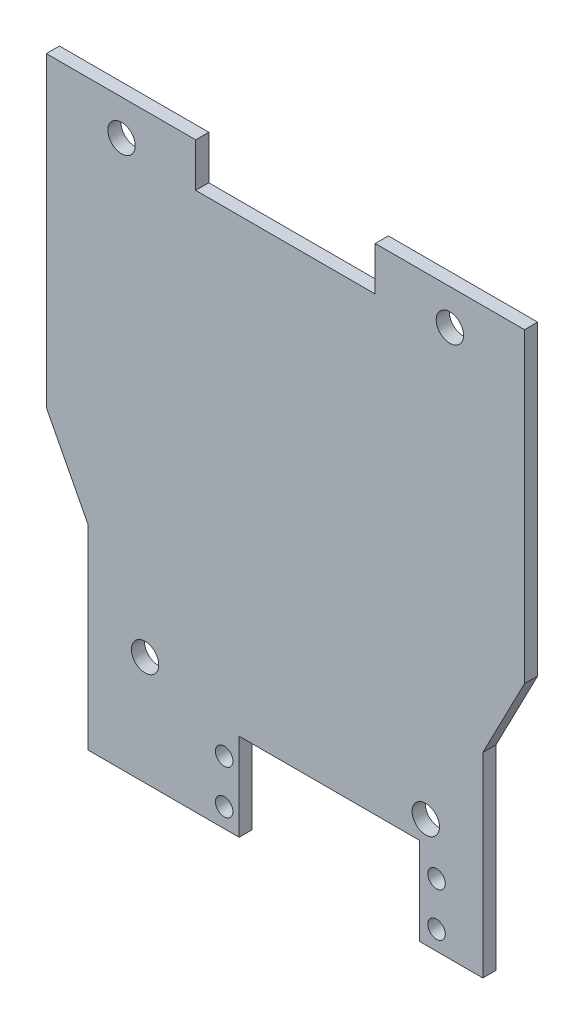
SolidWorks part; units mm, degrees
ref_plane "Front Plane" through (0, 0, 0) normal (0, 0, 1) x (1, 0, 0)
ref_plane "Top Plane" through (0, 0, 0) normal (0, 1, 0) x (1, 0, 0)
ref_plane "Right Plane" through (0, 0, 0) normal (1, 0, 0) x (0, 0, -1)
sketch "Sketch1" plane through (0, 0, 0) normal (0, 0, 1) x (1, 0, 0)
  line L0 (-17.1711, 8.1021) -> (16.943, 8.1021)
  line L1 (92.055, 8.1021) -> (92.055, -61.8979)
  line L2 (92.055, -61.8979) -> (82.5251, -80.2887)
  line L3 (82.5251, -80.2887) -> (82.5251, -124.8979)
  line L4 (-7.6412, -124.8979) -> (26.8588, -124.8979)
  line L5 (37.442, -1.8979) -> (37.442, -91.9634) construction
  line L6 (-17.1711, -61.8979) -> (-17.1711, 8.1021)
  line L7 (-17.1711, -61.8979) -> (-7.6412, -80.2887)
  line L8 (-7.6412, -124.8979) -> (-7.6412, -80.2887)
  line L9 (68.0251, -124.8979) -> (82.5251, -124.8979)
  line L10 (57.945, 8.1021) -> (92.055, 8.1021)
  line L11 (16.943, -1.8979) -> (57.945, -1.8979)
  line L12 (16.943, -1.8979) -> (16.943, 8.1021)
  line L14 (57.945, -1.8979) -> (57.945, 8.1021)
  line L15 (68.0251, -124.8979) -> (26.8588, -124.8979) construction
  line L16 (68.0251, -124.8979) -> (68.0251, -104.8979)
  line L17 (68.0251, -104.8979) -> (26.8588, -104.8979)
  line L18 (26.8588, -124.8979) -> (26.8588, -104.8979)
  circle A0 centre (0, 0) radius 3.125
  circle A1 centre (75, 0) radius 3.125
  point P9 (75, 8.1021)
  dimension "D1" = 75
  dimension "D2" = 6.25
  dimension "D3" = 10
  dimension "D4" = 34.1141
  dimension "D5" = 70
  dimension "D6" = 18.3908
  dimension "D7" = 27.393
  dimension "D8" = 34.11
  dimension "D9" = 133
  dimension "D10" = 14.5
  dimension "D11" = 34.5
  dimension "D12" = 20
extrude "Boss-Extrude1" add sketch "Sketch1" along normal blind 3
sketch "Sketch2" plane through (0, 0, 3) normal (0, 0, 1) x (1, 0, 0)
  line L0 (68.0251, -124.8979) -> (82.5251, -124.8979) construction
  line L3 (82.5251, -124.8979) -> (82.5251, -80.2887) construction
  circle A0 centre (71.9515, -120.5404) radius 2
  circle A1 centre (71.9515, -110.5412) radius 2
  circle A2 centre (23.4551, -120.5404) radius 2
  circle A3 centre (23.4551, -110.5412) radius 2
  dimension "D1" = 4
  dimension "D5" = 4
  dimension "D2" = 9.9992
  dimension "D3" = 4.3575
  dimension "D4" = 10.5736
  dimension "D6" = 9.9992
  dimension "D7" = 48.4964
extrude "Cut-Extrude1" cut sketch "Sketch2" against normal up to surface (3 mm away) up to face at (39.9425, -60.3218, 0)
sketch "Sketch3" plane through (0, 0, 0) normal (0, 0, -1) x (-1, 0, 0)
  line L0 (-37.444, -1.8979) -> (-37.444, -120.0162) construction
  line L1 (-57.945, -1.8979) -> (-16.943, -1.8979) construction
  line L3 (-68.0251, -124.8979) -> (-82.5251, -124.8979) construction
  line L4 (-82.5251, -124.8979) -> (-82.5251, -80.2887) construction
  circle A0 centre (-69.5, -100) radius 3.125
  circle A2 centre (-5.388, -100) radius 3.125
  dimension "D3" = 6.25
  dimension "D1" = 24.8979
  dimension "D2" = 13.0251
extrude "Cut-Extrude2" cut sketch "Sketch3" against normal up to surface (3 mm away) up to face at (73.9515, -110.5412, 3)
